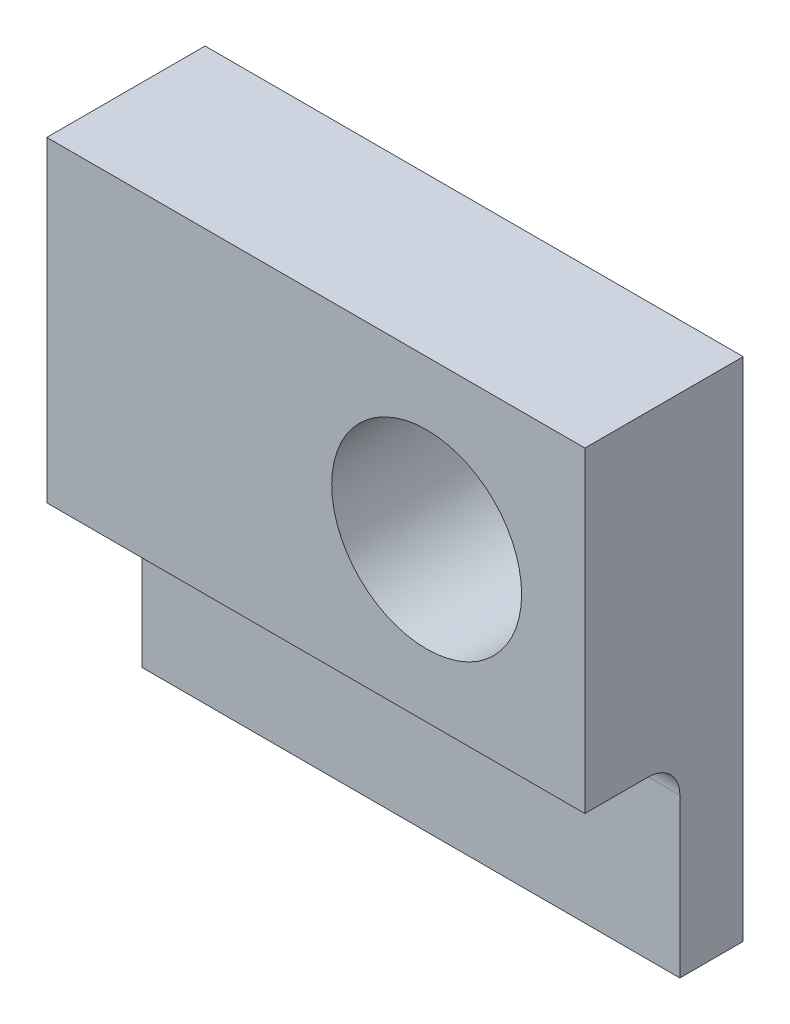
SolidWorks part; units mm, degrees
ref_plane "Plan de face" through (0, 0, 0) normal (0, 0, 1) x (1, 0, 0)
ref_plane "Plan de dessus" through (0, 0, 0) normal (0, 1, 0) x (1, 0, 0)
ref_plane "Plan de droite" through (0, 0, 0) normal (1, 0, 0) x (0, 0, -1)
sketch "Esquisse1" plane through (0, 0, 0) normal (0, 0, 1) x (1, 0, 0)
  line L1 (0, 0) -> (17, 0)
  line L2 (0, 0) -> (0, 10)
  line L3 (0, 10) -> (17, 10)
  line L4 (17, 0) -> (17, 10)
  circle A0 centre (12, 5) radius 3
  dimension "D1" = 6
  dimension "D2" = 10
  dimension "D3" = 5
  dimension "D4" = 5
  dimension "D5" = 17
extrude "Boss.-Extru.1" add sketch "Esquisse1" along normal blind 5
sketch "Esquisse2" plane through (0, 0, 0) normal (0, 0, -1) x (-1, 0, 0)
  line L1 (-17, 10) -> (0, 10)
  line L2 (-17, 10) -> (-17, -6)
  line L3 (-17, -6) -> (0, -6)
  line L4 (0, 10) -> (0, -6)
  line L5 (-17, 0) -> (0, 0)
  line L6 (-17, 0) -> (-17, -6)
  line L7 (-17, -6) -> (0, -6)
  line L8 (0, 0) -> (0, -6)
  line M5 (-17, 0) -> (0, 0)
  dimension "D1" = 16
extrude "Boss.-Extru.2" add sketch "Esquisse2" against normal blind 2 contours L4 L2 L3 M5
fillet "Congé1" radius 1 1 edges at (8.5, 0, 2)
